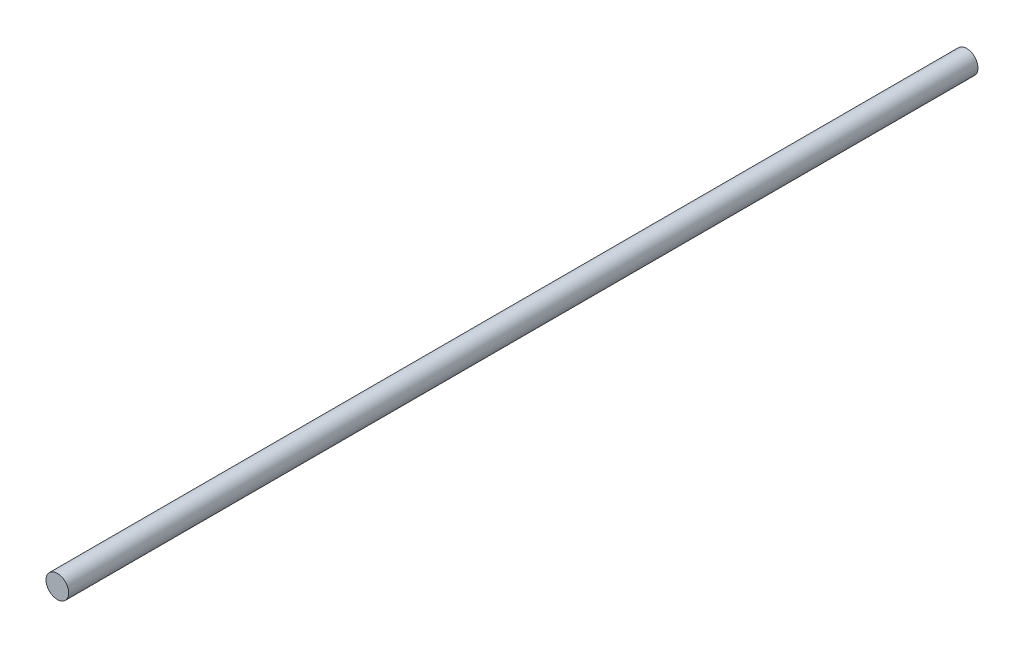
SolidWorks part; units mm, degrees
ref_plane "Alzado" through (0, 0, 0) normal (0, 0, 1) x (1, 0, 0)
ref_plane "Planta" through (0, 0, 0) normal (0, 1, 0) x (1, 0, 0)
ref_plane "Vista lateral" through (0, 0, 0) normal (1, 0, 0) x (0, 0, -1)
sketch "Croquis1" plane through (0, 0, 0) normal (0, 0, 1) x (1, 0, 0)
  circle A0 centre (0, 0) radius 12.5
  dimension "D1" = 25
extrude "Saliente-Extruir1" add sketch "Croquis1" along normal mid plane 1000
